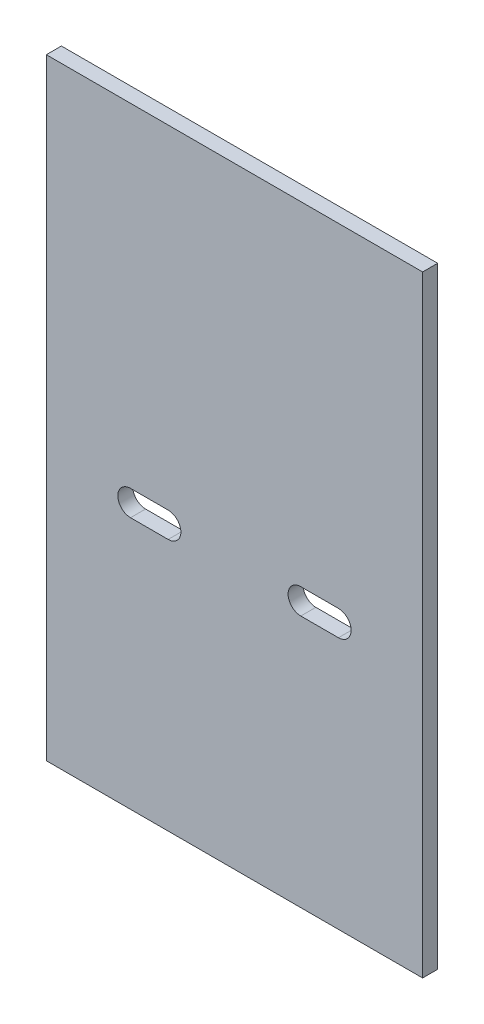
SolidWorks part; units mm, degrees
material "普通碳钢"
ref_plane "前视基准面" through (0, 0, 0) normal (0, 0, 1) x (1, 0, 0)
ref_plane "上视基准面" through (0, 0, 0) normal (0, 1, 0) x (1, 0, 0)
ref_plane "右视基准面" through (0, 0, 0) normal (1, 0, 0) x (0, 0, -1)
sketch "草图1" plane through (0, 0, 0) normal (0, 0, 1) x (1, 0, 0)
  line L1 (-200, -325) -> (200, -325)
  line L2 (-200, -325) -> (-200, 325)
  line L3 (-200, 325) -> (200, 325)
  line L4 (200, -325) -> (200, 325)
  line L5 (-200, -325) -> (200, 325) construction
  line L6 (-200, 325) -> (200, -325) construction
  point P0 (0, 0)
  dimension "D1" = 400
  dimension "D2" = 650
extrude "凸台-拉伸1" add sketch "草图1" against normal blind 16
sketch "草图2" plane through (0, 0, 0) normal (0, 0, 1) x (1, 0, 0)
  line L0 (0, -325) -> (0, 325) construction
  line L1 (-200, -325) -> (200, -325) construction
  line L2 (200, 325) -> (-200, 325) construction
  line L3 (-70.5, -43) -> (90.5, -43) construction
  line L4 (70.5, -43) -> (110.5, -43) construction
  line L5 (70.5, -29.5) -> (110.5, -29.5)
  line L6 (70.5, -56.5) -> (110.5, -56.5)
  line L7 (-70.5, -43) -> (-110.5, -43) construction
  line L11 (-70.5, -56.5) -> (-110.5, -56.5)
  line L12 (-70.5, -29.5) -> (-110.5, -29.5)
  arc A0 (70.5, -29.5) -> (70.5, -56.5) centre (70.5, -43) ccw
  arc A1 (110.5, -56.5) -> (110.5, -29.5) centre (110.5, -43) ccw
  arc A4 (-70.5, -56.5) -> (-70.5, -29.5) centre (-70.5, -43) ccw
  arc A5 (-110.5, -29.5) -> (-110.5, -56.5) centre (-110.5, -43) ccw
  point P10 (90.5, -43)
  point P15 (-90.5, -43)
  dimension "D1" = 27
  dimension "D2" = 40
  dimension "D3" = 368
  dimension "D4" = 181
extrude "切除-拉伸1" cut sketch "草图2" against normal through all
